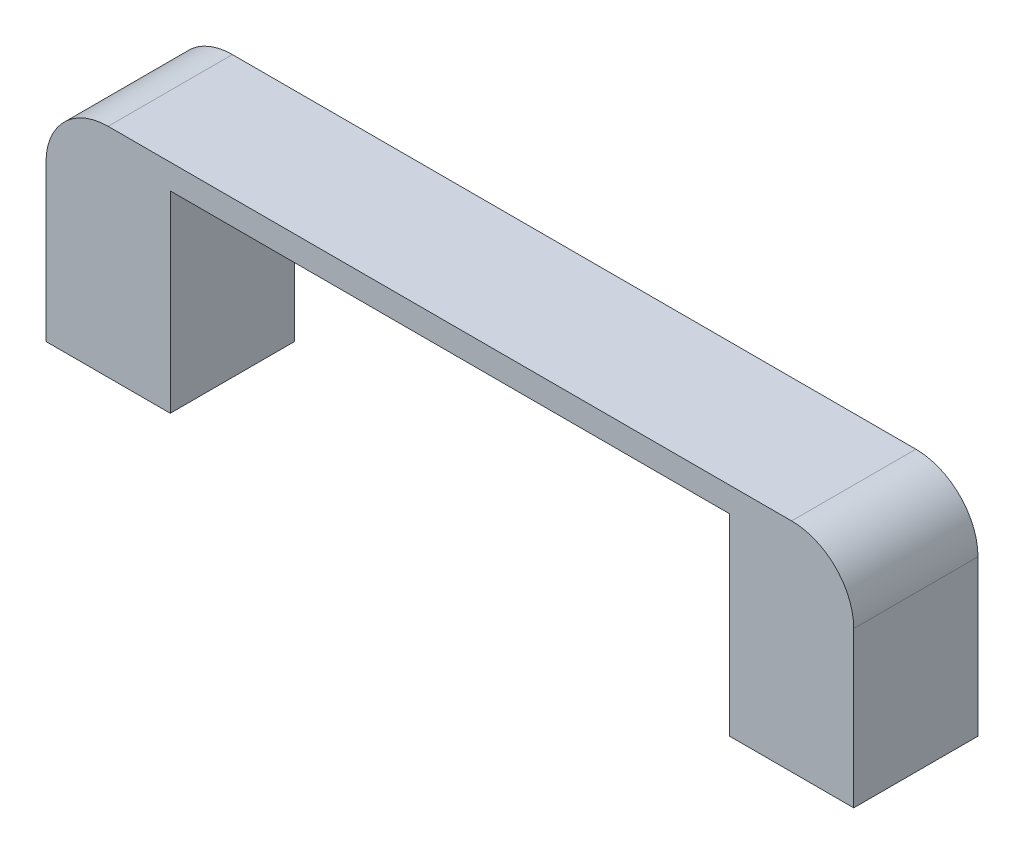
SolidWorks part; units mm, degrees
material "PLA"
ref_plane "Alzado" through (0, 0, 0) normal (0, 0, 1) x (1, 0, 0)
ref_plane "Planta" through (0, 0, 0) normal (0, 1, 0) x (1, 0, 0)
ref_plane "Vista lateral" through (0, 0, 0) normal (1, 0, 0) x (0, 0, -1)
sketch "Croquis1" plane through (0, 0, 0) normal (0, 1, 0) x (1, 0, 0)
  line L8 (0, 0) -> (22.5, 0) construction
  line L26 (22.5, 0) -> (-22.5, 0) construction
  line L27 (-22.5, 0) -> (-22.5, 10)
  line L28 (-22.5, 10) -> (-32.5, 10)
  line L29 (-32.5, 10) -> (-32.5, 0)
  line L30 (-32.5, 0) -> (-22.5, 0)
  line L31 (22.5, 0) -> (22.5, 10)
  line L32 (22.5, 10) -> (32.5, 10)
  line L33 (32.5, 10) -> (32.5, 0)
  line L34 (32.5, 0) -> (22.5, 0)
  dimension "D1" = 45
  dimension "D2" = 22.5
  dimension "D3" = 10
  dimension "D4" = 10
  dimension "D5" = 10
  dimension "D6" = 10
extrude "Saliente-Extruir1" add sketch "Croquis1" along normal blind 15.5
sketch "Croquis5" plane through (0, 15.5, 0) normal (0, 1, 0) x (1, 0, 0)
  line L0 (-32.5, 10) -> (32.5, 10)
  line L1 (32.5, 10) -> (32.5, 0)
  line L2 (32.5, 0) -> (-32.5, 0)
  line L3 (-32.5, 0) -> (-32.5, 10)
extrude "Saliente-Extruir4" add sketch "Croquis5" along normal blind 2
sketch "Croquis6" plane through (0, 0, 0) normal (0, -1, 0) x (1, 0, 0)
  line L0 (32.5, -10) -> (22.5, 0) construction
  line L1 (-22.5, 0) -> (-32.5, -10) construction
  circle A0 centre (-27.5, -5) radius 1.5
  circle A1 centre (27.5, -5) radius 1.5
  dimension "D1" = 3
  dimension "D2" = 3
extrude "Cortar-Extruir2" cut sketch "Croquis6" against normal blind 5
fillet "Redondeo1" radius 5 2 edges at (32.5, 17.5, -5) (-32.5, 17.5, -5)
